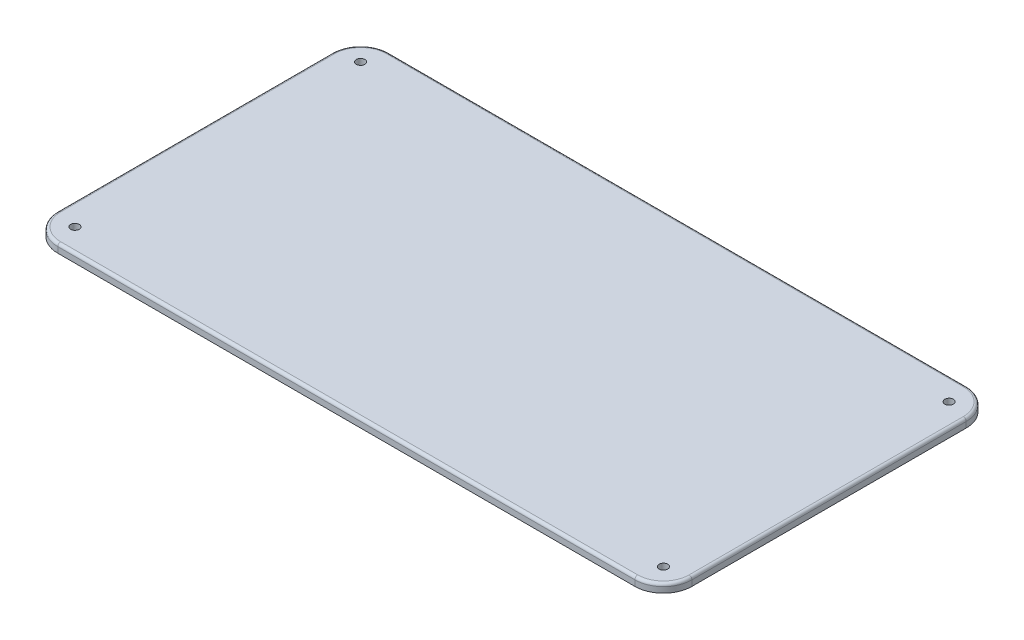
SolidWorks part; units mm, degrees
ref_plane "Front Plane" through (0, 0, 0) normal (0, 0, 1) x (1, 0, 0)
ref_plane "Top Plane" through (0, 0, 0) normal (0, 1, 0) x (1, 0, 0)
ref_plane "Right Plane" through (0, 0, 0) normal (1, 0, 0) x (0, 0, -1)
sketch "Sketch1" plane through (0, 57, 0) normal (0, 1, 0) x (1, 0, 0)
  line L0 (-31.5, -17) -> (-26.5, -17)
  line L12 (-26.5, -14) -> (-26.5, -17)
  line L13 (-26.5, -17) -> (7, -17)
  line L14 (17, -7) -> (17, 89)
  line L15 (7, 99) -> (-195, 99)
  line L16 (-205, 89) -> (-205, -7)
  line L17 (-195, -17) -> (-31.5, -17)
  line L18 (-31.5, -17) -> (-31.5, -14)
  line L19 (-31.5, -14) -> (-187, -14)
  line L20 (-202, 1) -> (-202, 81)
  line L21 (-187, 96) -> (-1, 96)
  line L22 (14, 81) -> (14, 1)
  line L23 (-1, -14) -> (-26.5, -14)
  line L25 (-26.5, -17) -> (7, -17)
  line L26 (17, -7) -> (17, 89)
  line L27 (7, 99) -> (-195, 99)
  line L28 (-205, 89) -> (-205, -7)
  line L29 (-195, -17) -> (-31.5, -17)
  circle A0 centre (-197, 91) radius 1.5 construction
  circle A1 centre (-197, 91) radius 1.5
  circle A2 centre (9, 91) radius 1.5 construction
  circle A3 centre (9, 91) radius 1.5
  circle A4 centre (9, -9) radius 1.5 construction
  circle A5 centre (9, -9) radius 1.5
  circle A6 centre (-197, -9) radius 1.5 construction
  circle A7 centre (-197, -9) radius 1.5
  arc A16 (7, -17) -> (17, -7) centre (7, -7) ccw
  arc A17 (17, 89) -> (7, 99) centre (7, 89) ccw
  arc A18 (-195, 99) -> (-205, 89) centre (-195, 89) ccw
  arc A19 (-205, -7) -> (-195, -17) centre (-195, -7) ccw
  arc A20 (-192, -9) -> (-187, -14) centre (-187, -9) ccw
  arc A21 (-192, -9) -> (-197, -4) centre (-197, -9) ccw
  arc A22 (-202, 1) -> (-197, -4) centre (-197, 1) ccw
  arc A23 (-197, 86) -> (-202, 81) centre (-197, 81) ccw
  arc A24 (-197, 86) -> (-192, 91) centre (-197, 91) ccw
  arc A25 (-187, 96) -> (-192, 91) centre (-187, 91) ccw
  arc A26 (4, 91) -> (-1, 96) centre (-1, 91) ccw
  arc A27 (4, 91) -> (9, 86) centre (9, 91) ccw
  arc A28 (14, 81) -> (9, 86) centre (9, 81) ccw
  arc A29 (9, -4) -> (14, 1) centre (9, 1) ccw
  arc A30 (9, -4) -> (4, -9) centre (9, -9) ccw
  arc A31 (-1, -14) -> (4, -9) centre (-1, -9) ccw
  arc A32 (7, -17) -> (17, -7) centre (7, -7) ccw
  arc A33 (17, 89) -> (7, 99) centre (7, 89) ccw
  arc A34 (-195, 99) -> (-205, 89) centre (-195, 89) ccw
  arc A35 (-205, -7) -> (-195, -17) centre (-195, -7) ccw
  dimension "D1" = 0
extrude "Boss-Extrude1" add sketch "Sketch1" along normal blind 3
fillet "Fillet1" radius 1 8 edges at (-202.0711, 60, 14.0711) (-205, 60, -41) (-202.0711, 60, -96.0711) (-94, 60, -99) (14.0711, 60, -96.0711) (17, 60, -41) (14.0711, 60, 14.0711) (-94, 60, 17)
